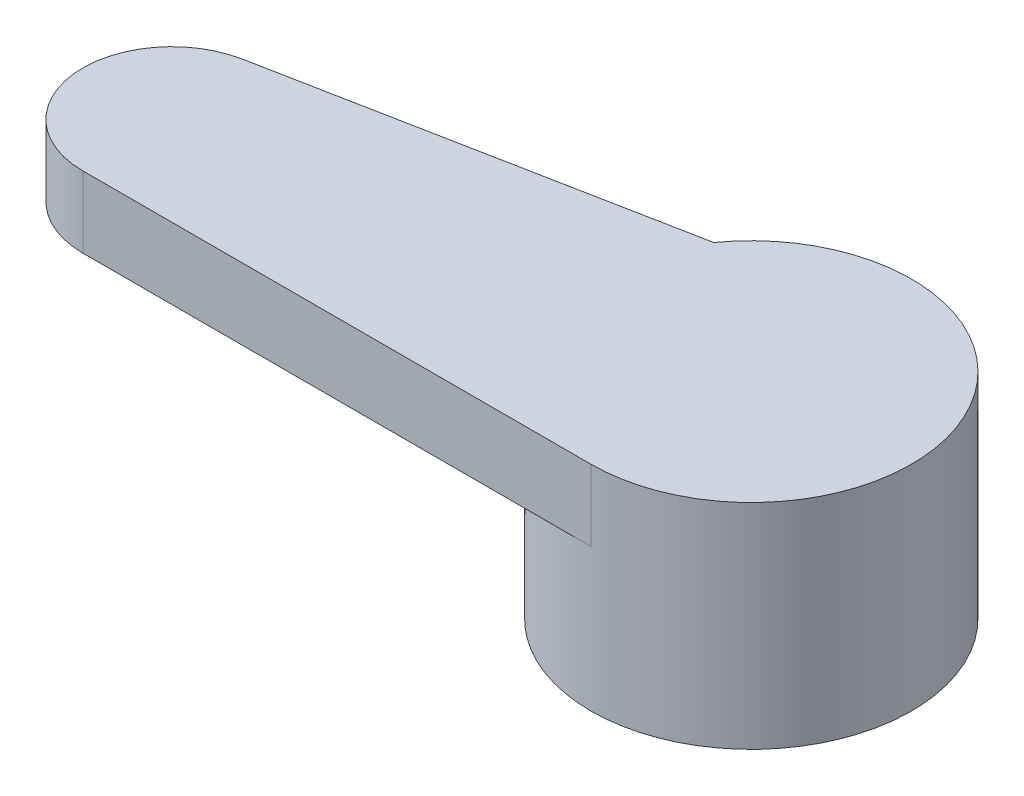
SolidWorks part; units mm, degrees
ref_plane "Front Plane" through (0, 0, 0) normal (0, 0, 1) x (1, 0, 0)
ref_plane "Top Plane" through (0, 0, 0) normal (0, 1, 0) x (1, 0, 0)
ref_plane "Right Plane" through (0, 0, 0) normal (1, 0, 0) x (0, 0, -1)
sketch "Sketch1" plane through (0, 0, 0) normal (0, 1, 0) x (1, 0, 0)
  circle A0 centre (0, 0) radius 4.5
  dimension "D1" = 9
extrude "Boss-Extrude1" add sketch "Sketch1" along normal blind 6
sketch "Sketch2" plane through (0, 6, 0) normal (0, 1, 0) x (1, 0, 0)
  line L0 (0, -4.5) -> (-14.2604, -4.5)
  line L1 (-14.7385, 0.4539) -> (-3.665, 2.6111)
  line L2 (-16.7362, -2.3472) -> (4.4564, 0.625) construction
  circle A0 centre (0, 0) radius 4.5 construction
  arc A1 (-14.2604, -4.5) -> (-14.7385, 0.4539) centre (-14.2604, -2) cw
  arc A2 (-3.665, 2.6111) -> (0, -4.5) centre (0, 0) ccw
  dimension "D1" = 21.4
  dimension "D2" = 2.5
  dimension "D3" = 8
extrude "Boss-Extrude2" add sketch "Sketch2" against normal blind 2
